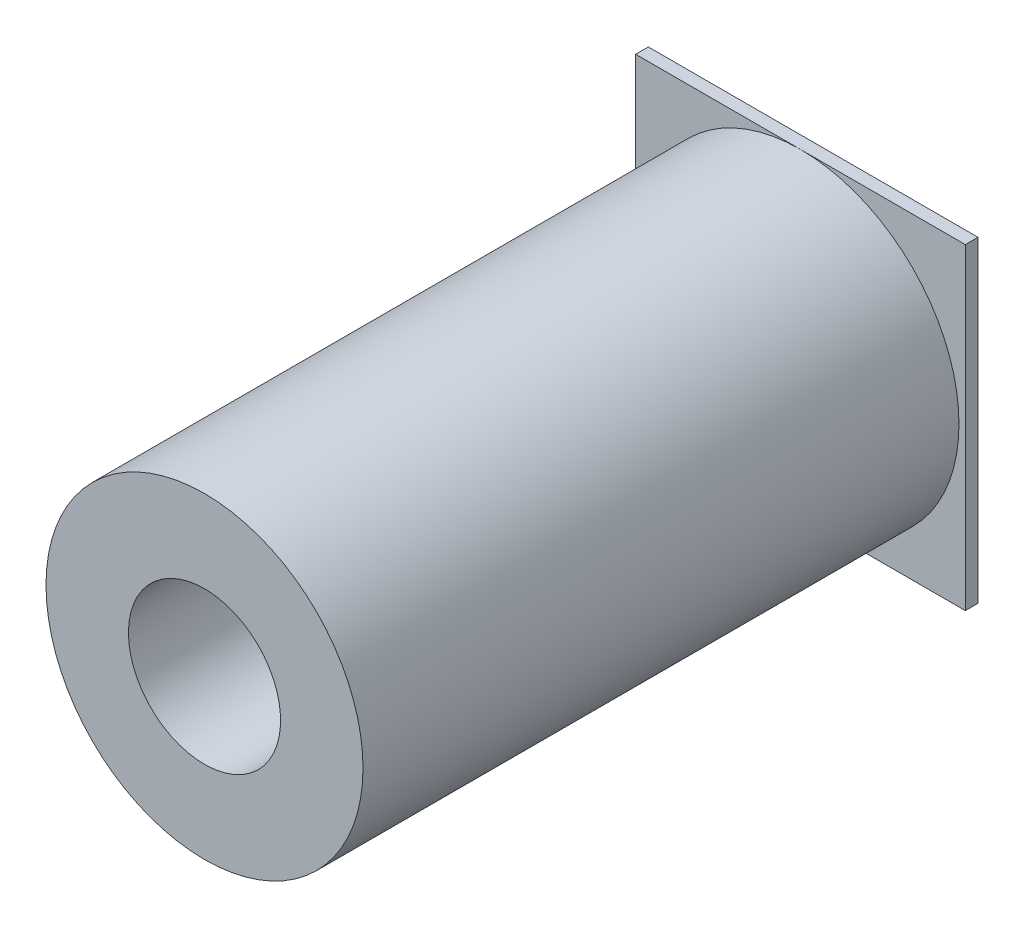
SolidWorks part; units mm, degrees
ref_plane "Front Plane" through (0, 0, 0) normal (0, 0, 1) x (1, 0, 0)
ref_plane "Top Plane" through (0, 0, 0) normal (0, 1, 0) x (1, 0, 0)
ref_plane "Right Plane" through (0, 0, 0) normal (1, 0, 0) x (0, 0, -1)
sketch "Sketch1" plane through (0, 0, 0) normal (0, 0, 1) x (1, 0, 0)
  line L1 (-13, 12.5) -> (13, 12.5)
  line L2 (-13, 12.5) -> (-13, -12.5)
  line L3 (-13, -12.5) -> (13, -12.5)
  line L4 (13, 12.5) -> (13, -12.5)
  line L5 (-13, 12.5) -> (13, -12.5) construction
  line L6 (-13, -12.5) -> (13, 12.5) construction
  point P0 (0, 0)
  dimension "D1" = 26
  dimension "D2" = 25
extrude "Boss-Extrude1" add sketch "Sketch1" along normal blind 1
sketch "Sketch2" plane through (0, 0, 1) normal (0, 0, 1) x (1, 0, 0)
  circle A0 centre (0, 0) radius 12.5
  dimension "D1" = 25
extrude "Boss-Extrude2" add sketch "Sketch2" along normal blind 47
sketch "Sketch3" plane through (0, 0, 0) normal (0, 0, -1) x (-1, 0, 0)
  circle A0 centre (0, 0) radius 6
  dimension "D1" = 12
extrude "Cut-Extrude1" cut sketch "Sketch3" against normal through all
